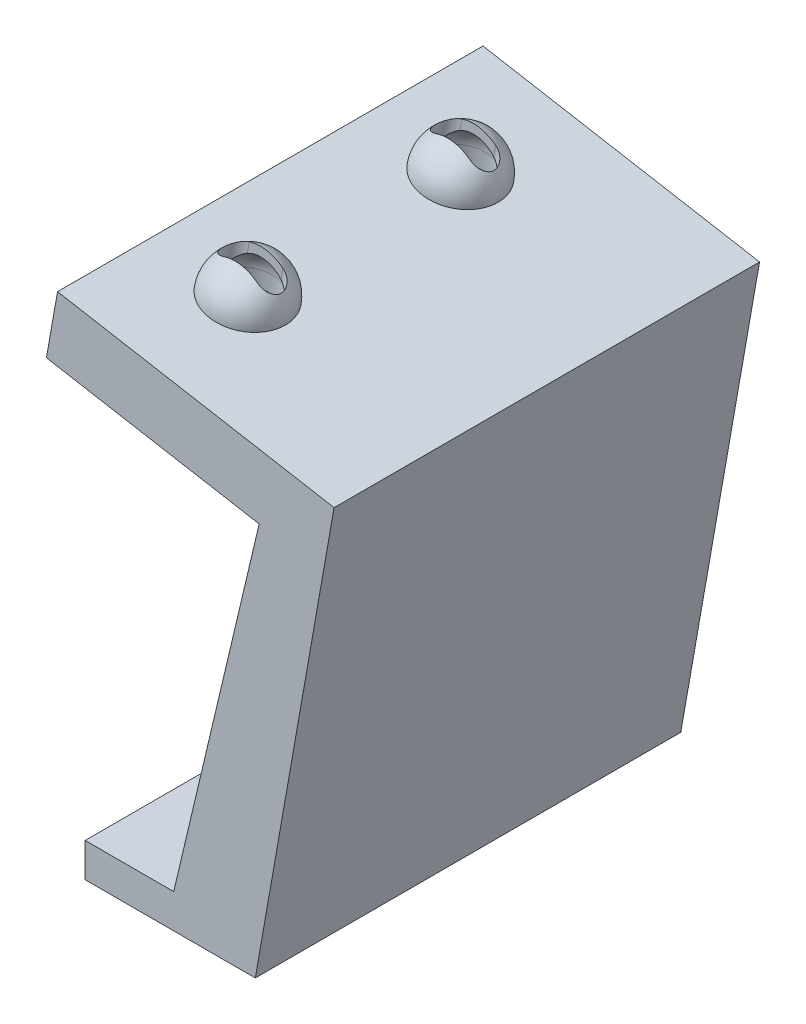
SolidWorks part; units mm, degrees
ref_plane "Front Plane" through (0, 0, 0) normal (0, 0, 1) x (1, 0, 0)
ref_plane "Top Plane" through (0, 0, 0) normal (0, 1, 0) x (1, 0, 0)
ref_plane "Right Plane" through (0, 0, 0) normal (1, 0, 0) x (0, 0, -1)
sketch "Sketch1" plane through (0, 0, 0) normal (0, 0, 1) x (1, 0, 0)
  line L1 (19.4718, 0) -> (37.9862, 105)
  line L2 (37.9862, 105) -> (-27.0138, 116.4613)
  line L3 (-27.0138, 116.4613) -> (-29.6185, 101.6891)
  line L4 (-29.6185, 101.6891) -> (20.3815, 92.8728)
  line L5 (20.3815, 92.8728) -> (0.2969, 8)
  line L7 (19.4718, 0) -> (-20.5282, 0)
  line L8 (-20.5282, 0) -> (-20.5282, 8)
  line L9 (-20.5282, 8) -> (0.2969, 8)
  dimension "D1" = 105
  dimension "D2" = 65
  dimension "D3" = 15
  dimension "D4" = 50
  dimension "D5" = 87.2169
  dimension "D6" = 100
  dimension "D7" = 8
  dimension "D8" = 40
  dimension "D9" = 20.5282
extrude "Boss-Extrude1" add sketch "Sketch1" along normal blind 100
ref_plane "Plane1" through (0, 0, 25) normal (0, 0, 1) x (1, 0, 0)
sketch "Sketch2" plane through (0, 0, 25) normal (0, 0, 1) x (1, 0, 0)
  line L0 (-2.813, 138.5355) -> (-11.4797, 89.3841) construction
  line L2 (37.9862, 105) -> (-27.0138, 116.4613) construction
  line L3 (-27.0138, 116.4613) -> (-29.6185, 101.6891) construction
  line L4 (-5.7403, 121.9338) -> (-6.0871, 119.9674)
  line L5 (-14.2108, 114.2037) -> (-16.1774, 114.5505)
  arc A0 (-5.7403, 121.9338) -> (-16.1774, 114.5505) centre (-7.3026, 113.0737) ccw
  arc A1 (-6.0871, 119.9674) -> (-14.2108, 114.2037) centre (-7.3026, 113.0737) ccw
  dimension "D2" = 7
  dimension "D3" = 8.9968
  dimension "D1" = 20
  dimension "D4" = 1.9969
revolve "Revolve1" add sketch "Sketch2" angle 360 about L0
sketch "Sketch6" plane through (0, 0, 25) normal (0, 0, 1) x (1, 0, 0)
  line L0 (-4.9456, 126.4409) -> (-12.8458, 81.6367) construction
  line L1 (37.9862, 105) -> (-27.0138, 116.4613) construction
  line L3 (-29.6185, 101.6891) -> (20.3815, 92.8728) construction
  line L4 (-7.665, 111.0187) -> (-9.9224, 98.2162)
  line L5 (-9.9224, 98.2162) -> (-22.7249, 100.4736)
  arc A0 (1.542, 111.4261) -> (-16.1774, 114.5505) centre (-7.3026, 113.0737) ccw construction
  arc A2 (-7.665, 111.0187) -> (-22.7249, 100.4736) centre (-9.9224, 98.2162) ccw
  dimension "D1" = 26
revolve "Cut-Revolve3" cut sketch "Sketch6" angle 360 about L0
sketch "Sketch7" plane through (0, 0, 0) normal (0, 1, 0) x (1, 0, 0)
  line L0 (0, 0) -> (0, -121.1899) construction
sketch "Sketch8" plane through (19.1015, 108.3299, 0) normal (0.1736, 0.9848, 0) x (0.9848, -0.1736, 0)
  circle A0 centre (-26.83, -25) radius 7
  dimension "D1" = 14
  dimension "D2" = 26.83
  dimension "D3" = 25
extrude "Cut-Extrude1" cut sketch "Sketch8" against normal up to next
sketch "Sketch9" plane through (19.1015, 108.3299, 0) normal (0.1736, 0.9848, 0) x (0.9848, -0.1736, 0)
  line L0 (-53.755, -25) -> (29.0865, -25) construction
  line L1 (-22.83, -25) -> (-30.83, -25) construction
  line L2 (-22.83, -28) -> (-30.83, -28)
  line L3 (-22.83, -22) -> (-30.83, -22)
  arc A0 (-22.83, -28) -> (-22.83, -22) centre (-22.83, -25) ccw
  arc A1 (-30.83, -22) -> (-30.83, -28) centre (-30.83, -25) ccw
  point P5 (-26.83, -25)
  dimension "D3" = 3
  dimension "D1" = 25
  dimension "D2" = 8
  dimension "D4" = 26.83
extrude "Cut-Extrude2" cut sketch "Sketch9" along normal up to next
ref_plane "Plane2" through (0, 0, 50) normal (0, 0, 1) x (1, 0, 0)
sketch "Sketch10" plane through (0, 8, 0) normal (0, 1, 0) x (1, 0, 0)
  line L0 (-20.5282, -100) -> (-20.5282, 0) construction
  line L1 (-20.5282, 0) -> (19.4718, 0) construction
  circle A0 centre (-10.5282, -25) radius 3.5
  dimension "D2" = 7
  dimension "D1" = 10
  dimension "D3" = 25
extrude "Cut-Extrude3" cut sketch "Sketch10" against normal up to next
mirror "Mirror1" about plane through (0, 0, 50) normal (0, 0, 1) of "Cut-Extrude3", "Revolve1", "Cut-Extrude1", "Cut-Extrude2", "Cut-Revolve3"
sketch "Sketch11" plane through (0, 0, 50) normal (0, 0, 1) x (1, 0, 0)
  line L0 (2.8801, 95.9587) -> (15.6488, 72.8739)
  line L1 (20.3815, 92.8728) -> (0.2969, 8) construction
  line L5 (-29.6185, 101.6891) -> (20.3815, 92.8728) construction
  line L6 (20.3815, 92.8728) -> (15.6488, 72.8739)
  line L7 (2.8801, 95.9587) -> (20.3815, 92.8728)
  dimension "D1" = 23.0849
extrude "Boss-Extrude2" add sketch "Sketch11" along normal mid plane 20
sketch "Sketch12" plane through (0, 0, 50) normal (0, 0, 1) x (1, 0, 0)
  line L0 (5.0297, 28) -> (-14.9135, 8)
  line L1 (20.3815, 92.8728) -> (0.2969, 8) construction
  line L2 (0.2969, 8) -> (-20.5282, 8) construction
  line L3 (-14.9135, 8) -> (0.2969, 8)
  line L4 (0.2969, 8) -> (5.0297, 28)
  dimension "D1" = 20
  dimension "D2" = 15.2104
extrude "Boss-Extrude3" add sketch "Sketch12" along normal mid plane 20
